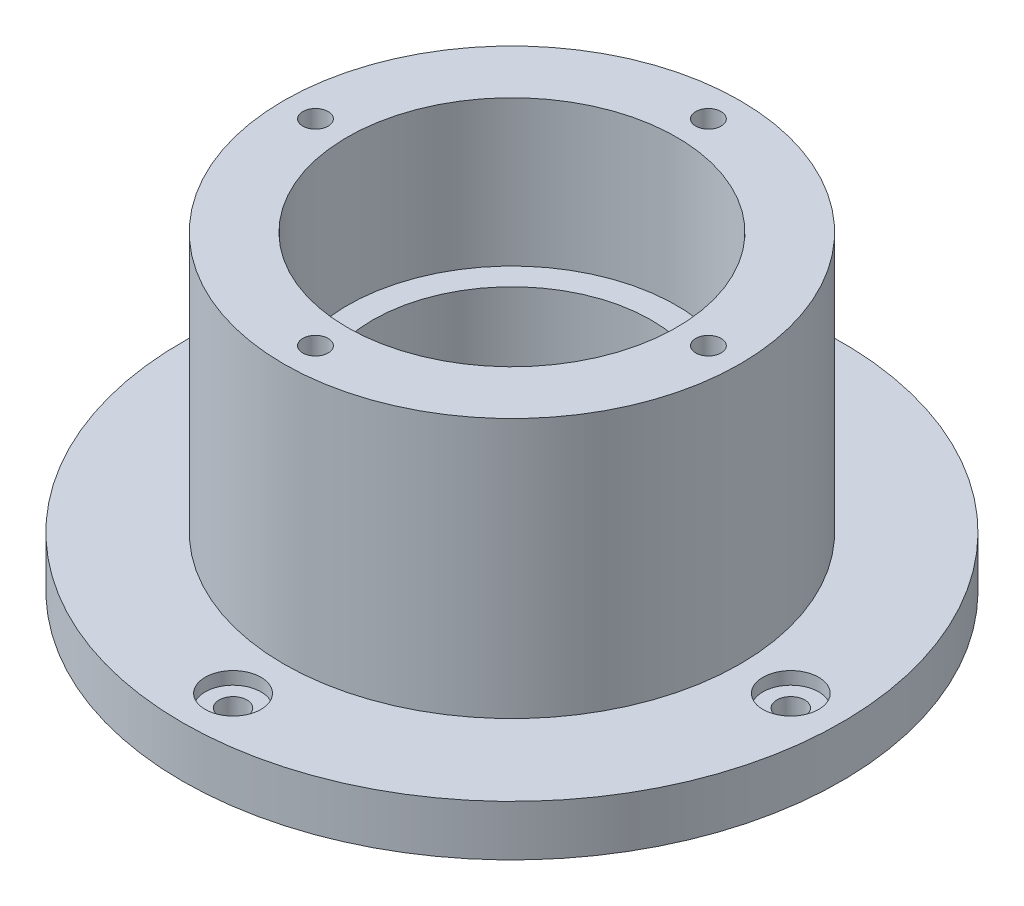
SolidWorks part; units mm, degrees
material "ABS"
ref_plane "Спереди" through (0, 0, 0) normal (0, 0, 1) x (1, 0, 0)
ref_plane "Сверху" through (0, 0, 0) normal (0, 1, 0) x (1, 0, 0)
ref_plane "Справа" through (0, 0, 0) normal (1, 0, 0) x (0, 0, -1)
sketch "Эскиз1" plane through (0, 0, 0) normal (0, 1, 0) x (1, 0, 0)
  circle A0 centre (0, 0) radius 26
  dimension "D1" = 52
extrude "Бобышка-Вытянуть1" add sketch "Эскиз1" along normal blind 4
sketch "Эскиз2" plane through (0, 4, 0) normal (0, 1, 0) x (1, 0, 0)
  circle A0 centre (0, 0) radius 18
  dimension "D1" = 36
extrude "Бобышка-Вытянуть2" add sketch "Эскиз2" along normal blind 20.5
sketch "Эскиз3" plane through (0, 24.5, 0) normal (0, 1, 0) x (1, 0, 0)
  circle A0 centre (0, 0) radius 13
  dimension "D1" = 26
extrude "Вырез-Вытянуть1" cut sketch "Эскиз3" along direction (0, 1, 0) on the side against the normal offset from surface (11.5 mm away) 13
sketch "Эскиз4" plane through (0, 4, 0) normal (0, 1, 0) x (1, 0, 0)
  circle A0 centre (0, 0) radius 22 construction
  circle A1 centre (-22, 0) radius 2.2
  circle A2 centre (0, 22) radius 2.2
  circle A3 centre (22, 0) radius 2.2
  circle A4 centre (0, -22) radius 2.2
  point P14 (0, 0)
  dimension "D1" = 44
  dimension "D2" = 4.4
extrude "Вырез-Вытянуть2" cut sketch "Эскиз4" against normal blind 1
sketch "Эскиз5" plane through (0, 4, 0) normal (0, 1, 0) x (1, 0, 0)
  circle A0 centre (-22, 0) radius 1.1
  circle A1 centre (0, 22) radius 1.1
  circle A2 centre (22, 0) radius 1.1
  circle A3 centre (0, -22) radius 1.1
  point P12 (0, 0)
  dimension "D1" = 2.2
extrude "Вырез-Вытянуть3" cut sketch "Эскиз5" against normal through all
sketch "Эскиз6" plane through (0, 13, 0) normal (0, 1, 0) x (1, 0, 0)
  circle A0 centre (0, 0) radius 11
  dimension "D1" = 22
extrude "Вырез-Вытянуть4" cut sketch "Эскиз6" against normal through all
sketch "Эскиз7" plane through (0, 24.5, 0) normal (0, 1, 0) x (1, 0, 0)
  circle A0 centre (0, 0) radius 15.5 construction
  circle A1 centre (-15.5, 0) radius 1
  circle A2 centre (0, 15.5) radius 1
  circle A3 centre (15.5, 0) radius 1
  circle A4 centre (0, -15.5) radius 1
  point P14 (0, 0)
  dimension "D1" = 31
  dimension "D2" = 2
extrude "Вырез-Вытянуть5" cut sketch "Эскиз7" against normal blind 5
